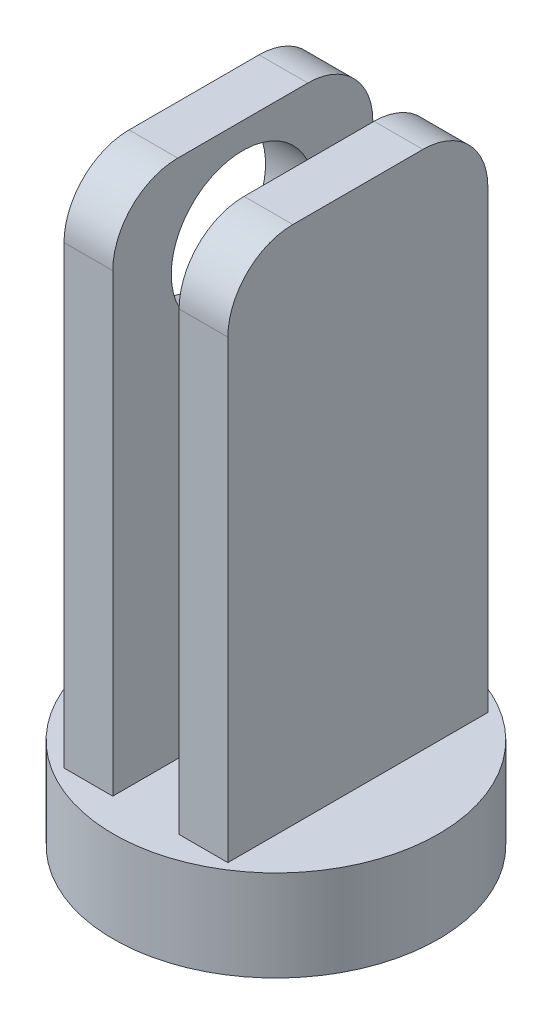
SolidWorks part; units mm, degrees
ref_plane "Front Plane" through (0, 0, 0) normal (0, 0, 1) x (1, 0, 0)
ref_plane "Top Plane" through (0, 0, 0) normal (0, 1, 0) x (1, 0, 0)
ref_plane "Right Plane" through (0, 0, 0) normal (1, 0, 0) x (0, 0, -1)
sketch "Sketch1" plane through (0, 0, 0) normal (0, 1, 0) x (1, 0, 0)
  circle A0 centre (0, 0) radius 25
  dimension "D1" = 50
extrude "Boss-Extrude1" add sketch "Sketch1" along normal blind 14
sketch "Sketch2" plane through (0, 0, 0) normal (0, -1, 0) x (1, 0, 0)
  circle A0 centre (0, 0) radius 11
extrude "Cut-Extrude1" cut sketch "Sketch2" against normal blind 7
sketch "Sketch5" plane through (0, 14, 0) normal (0, 1, 0) x (1, 0, 0)
  line L0 (0, 0) -> (-5.1, 0) construction
  line L1 (0, 0) -> (5.1, 0) construction
  line L2 (-5.1, -20) -> (-5.1, 20)
  line L3 (-5.1, 20) -> (-12.6, 20)
  line L4 (-12.6, 20) -> (-12.6, -20)
  line L5 (-12.6, -20) -> (-5.1, -20)
  line L7 (12.6, -20) -> (12.6, 20)
  line L8 (12.6, 20) -> (5.1, 20)
  line L9 (5.1, 20) -> (5.1, -20)
  line L10 (5.1, -20) -> (12.6, -20)
  dimension "D1" = 5.1
  dimension "D2" = 5.1
  dimension "D3" = 7.5
  dimension "D4" = 20
  dimension "D5" = 20
  dimension "D6" = 0
  dimension "D7" = 7.5
  dimension "D8" = 20
  dimension "D9" = 20
extrude "Boss-Extrude2" add sketch "Sketch5" along normal blind 80
sketch "Sketch7" plane through (-12.6, 0, 0) normal (-1, 0, 0) x (0, 0, 1)
  line L0 (20, 94) -> (20, 14) construction
  line L1 (-20, 94) -> (20, 94) construction
  circle A0 centre (0, 79) radius 11
  dimension "D1" = 20
  dimension "D2" = 15
fillet "Fillet1" radius 10 4 edges at (-8.85, 94, -20) (8.85, 94, -20) (8.85, 94, 20) (-8.85, 94, 20)
extrude "Cut-Extrude3" cut sketch "Sketch7" against normal blind 24.5
